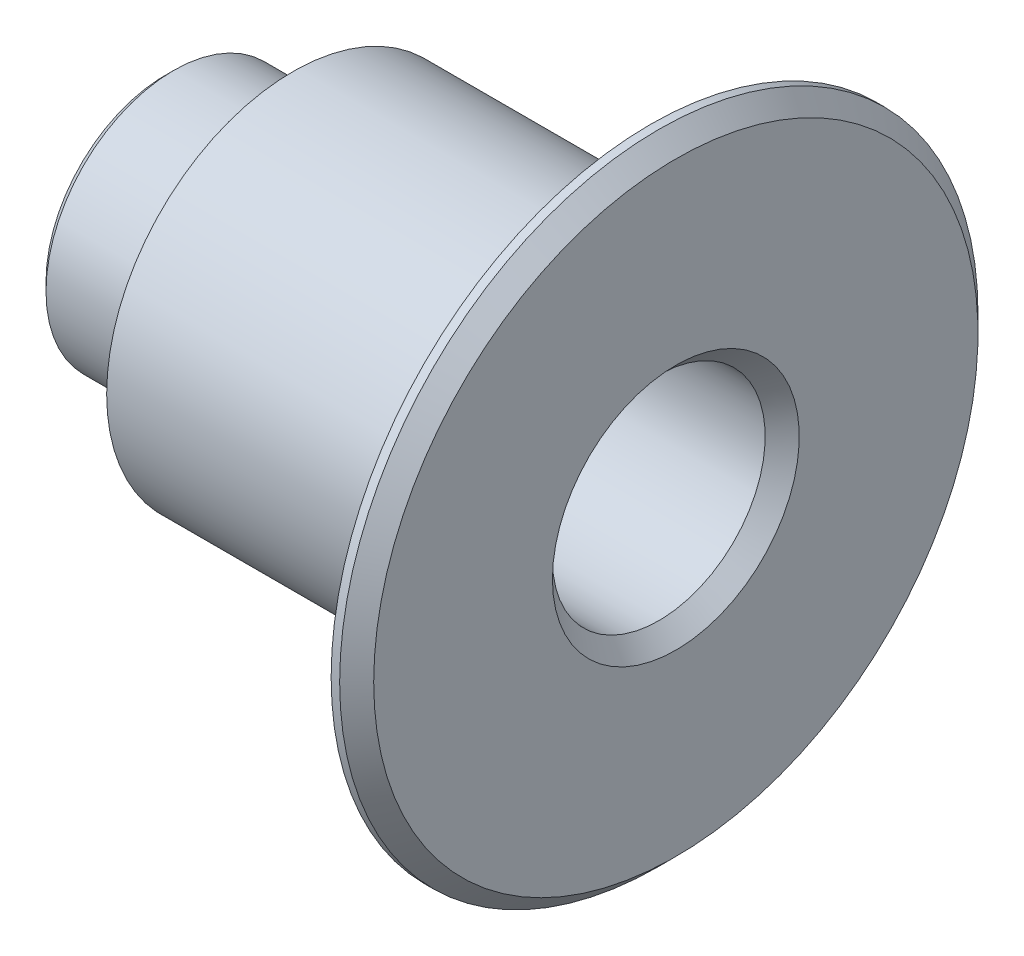
SolidWorks part; units mm, degrees
ref_plane "Front Plane" through (0, 0, 0) normal (0, 0, 1) x (1, 0, 0)
ref_plane "Top Plane" through (0, 0, 0) normal (0, 1, 0) x (1, 0, 0)
ref_plane "Right Plane" through (0, 0, 0) normal (1, 0, 0) x (0, 0, -1)
sketch "Sketch1" plane through (0, 0, 0) normal (0, 1, 0) x (1, 0, 0)
  line L0 (-57.9961, 3.3599) -> (-49.3833, 3.3599) construction
  line L1 (-57.9961, 8.9161) -> (-57.9961, 6.5349)
  line L2 (-57.9961, 6.5349) -> (-42.7561, 6.5349)
  line L3 (-42.7561, 6.5349) -> (-42.7561, 12.8849)
  line L4 (-42.7561, 12.8849) -> (-43.5181, 12.8849)
  line L5 (-43.5181, 12.8849) -> (-43.5181, 8.9161)
  line L6 (-43.5181, 8.9161) -> (-57.9961, 8.9161)
  line L7 (-57.9961, 8.9161) -> (-54.1861, 8.9161)
  line L8 (-57.9961, 8.9161) -> (-57.9961, 7.1699)
  line L9 (-57.9961, 7.1699) -> (-54.1861, 7.1699)
  line L10 (-54.1861, 8.9161) -> (-54.1861, 7.1699)
  dimension "D1" = 0.762
  dimension "D2" = 15.24
  dimension "D3" = 1.7462
  dimension "D4" = 3.81
  dimension "D5" = 6.35
revolve "Revolve1" add sketch "Sketch1" angle 360 about L0
chamfer "Chamfer1" distance 0.254 angle 45 2 edges at (-57.9961, 0, 0.4501) (-57.9961, 0, -0.1849)
chamfer "Chamfer2" distance 0.508 angle 45 1 edges at (-42.7561, 0, -0.1849)
chamfer "Chamfer3" distance 0.508 angle 45 1 edges at (-42.7561, 0, 6.1651)
